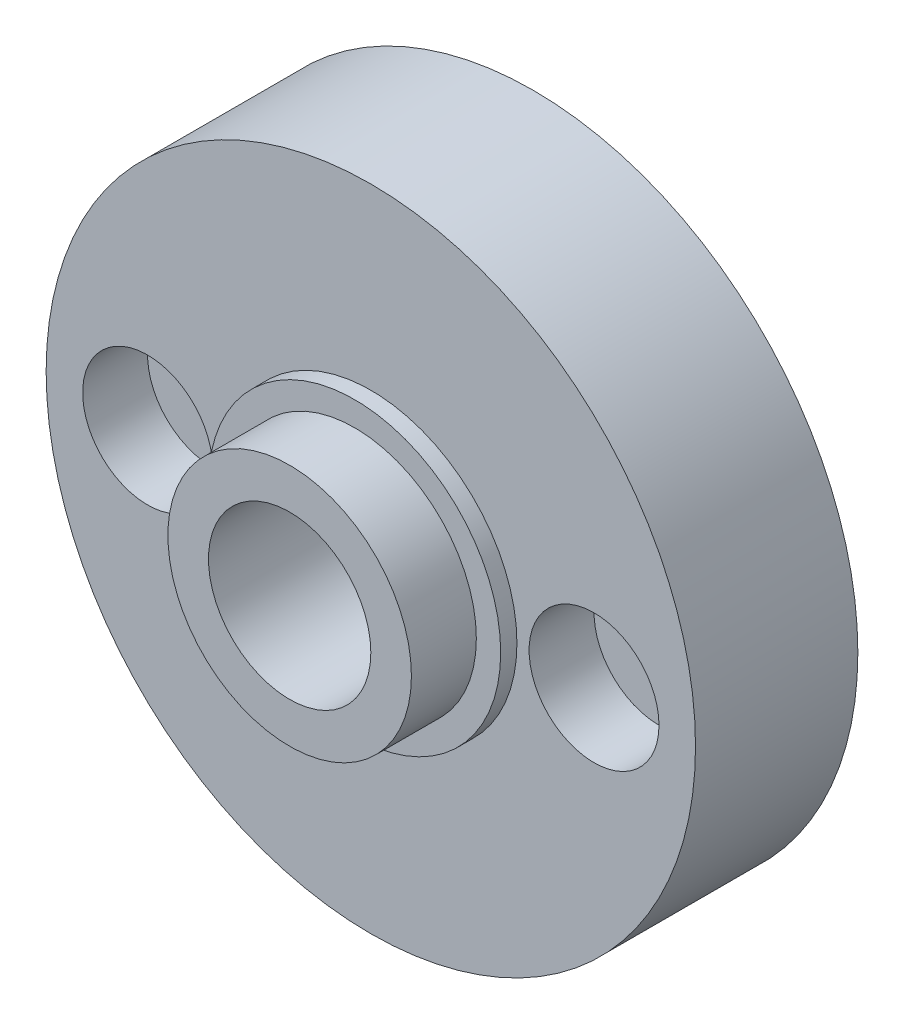
SolidWorks part; units mm, degrees
ref_plane "正面" through (0, 0, 0) normal (0, 0, 1) x (1, 0, 0)
ref_plane "平面" through (0, 0, 0) normal (0, 1, 0) x (1, 0, 0)
ref_plane "右側面" through (0, 0, 0) normal (1, 0, 0) x (0, 0, -1)
sketch "ｽｹｯﾁ1" plane through (0, 0, 0) normal (0, 0, 1) x (1, 0, 0)
  line L0 (-20, 0) -> (20, 0) construction
  circle A0 centre (0, 0) radius 20
  circle A1 centre (0, 0) radius 5
  circle A2 centre (-13.75, 0) radius 1.65
  circle A3 centre (13.75, 0) radius 1.65
  dimension "D1" = 40
  dimension "D2" = 10
  dimension "D3" = 3.3
  dimension "D4" = 13.75
  dimension "D5" = 27.5
extrude "ﾎﾞｽ - 押し出し1" add sketch "ｽｹｯﾁ1" along normal blind 10
sketch "ｽｹｯﾁ2" plane through (0, 0, 10) normal (0, 0, 1) x (1, 0, 0)
  circle A0 centre (0, 0) radius 9
  circle A1 centre (0, 0) radius 5
  dimension "D1" = 18
  dimension "D2" = 10
extrude "ﾎﾞｽ - 押し出し2" add sketch "ｽｹｯﾁ2" along normal blind 1
sketch "ｽｹｯﾁ3" plane through (0, 0, 11) normal (0, 0, 1) x (1, 0, 0)
  circle A0 centre (0, 0) radius 7.5
  circle A1 centre (0, 0) radius 5
  dimension "D1" = 15
  dimension "D2" = 10
extrude "ﾎﾞｽ - 押し出し3" add sketch "ｽｹｯﾁ3" along normal blind 4
sketch "ｽｹｯﾁ4" plane through (0, 0, 10) normal (0, 0, 1) x (1, 0, 0)
  circle A0 centre (-13.75, 0) radius 4
  circle A1 centre (13.75, 0) radius 4
  dimension "D1" = 8
  dimension "D2" = 8
extrude "ｶｯﾄ - 押し出し1" cut sketch "ｽｹｯﾁ4" against normal blind 4
